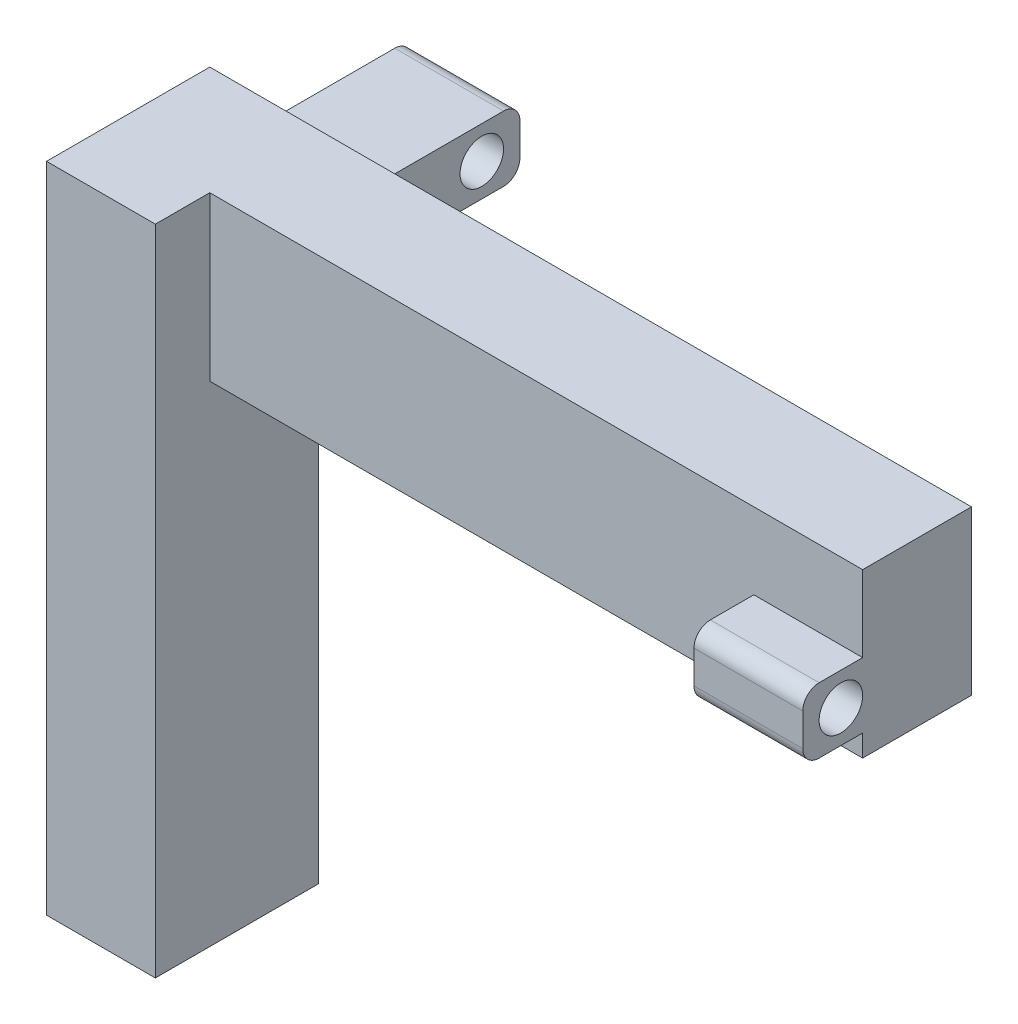
SolidWorks part; units mm, degrees
ref_plane "Front Plane" through (0, 0, 0) normal (0, 0, 1) x (1, 0, 0)
ref_plane "Top Plane" through (0, 0, 0) normal (0, 1, 0) x (1, 0, 0)
ref_plane "Right Plane" through (0, 0, 0) normal (1, 0, 0) x (0, 0, -1)
sketch "Sketch1" plane through (0, 0, 0) normal (0, 0, 1) x (1, 0, 0)
  line L1 (-5, 30) -> (5, 30)
  line L2 (-5, 30) -> (-5, -30)
  line L3 (-5, -30) -> (5, -30)
  line L4 (5, 30) -> (5, -30)
  line L5 (-5, 30) -> (5, -30) construction
  line L6 (-5, -30) -> (5, 30) construction
  point P0 (0, 0)
  dimension "D1" = 60
  dimension "D2" = 10
extrude "Boss-Extrude1" add sketch "Sketch1" along normal blind 15
sketch "Sketch2" plane through (0, 0, 0) normal (0, 0, 1) x (1, 0, 0)
  line L0 (5, 30) -> (-5, 30)
  line L1 (-5, 30) -> (-5, -30)
  line L2 (-5, -30) -> (5, -30)
  line L3 (5, -30) -> (5, 30)
ref_plane "Plane1" through (5, 0, 0) normal (1, 0, 0) x (0, 0, -1)
sketch "Sketch4" plane through (5, 0, 0) normal (1, 0, 0) x (0, 0, -1)
  line L0 (0, 30) -> (-10, 30)
  line L1 (-15, 30) -> (0, 30) construction
  line L2 (0, 30) -> (0, 15)
  line L3 (0, -30) -> (0, 30) construction
  line L4 (-10, 30) -> (-10, 15)
  line L5 (-10, 15) -> (0, 15)
  dimension "D1" = 10
  dimension "D2" = 15
extrude "Boss-Extrude2" add sketch "Sketch4" along normal blind 60
ref_plane "Plane2" through (65, 0, 0) normal (1, 0, 0) x (0, 0, -1)
sketch "Sketch5" plane through (65, 0, 0) normal (1, 0, 0) x (0, 0, -1)
  line L0 (-10, 30) -> (-10, 20)
  line L1 (-10, 30) -> (-10, 15) construction
  line L2 (-10, 20) -> (-12, 20)
  line L3 (-10, 20) -> (-14, 20)
  line L6 (-15.5, 21.5) -> (-15.5, 18.5)
  line L7 (-14, 23) -> (-10, 23)
  line L8 (-14, 17) -> (-10, 17)
  line L9 (-10, 17) -> (-10, 23)
  circle A1 centre (-12, 20) radius 2
  arc A2 (-14, 23) -> (-15.5, 21.5) centre (-14, 21.5) ccw
  arc A3 (-14, 17) -> (-15.5, 18.5) centre (-14, 18.5) cw
  dimension "D1" = 10
  dimension "D2" = 2
  dimension "D3" = 3
  dimension "D4" = 3
extrude "Boss-Extrude4" add sketch "Sketch5" against normal blind 10 contours A3 L8 L9 A1 L0 L7 A2 L6 | L2 A1 L3 | L3 A1 L2
sketch "Sketch6" plane through (65, 0, 0) normal (1, 0, 0) x (0, 0, -1)
  line L0 (-10, 23) -> (-10, 17)
  line L1 (-10, 20) -> (-12, 20)
  circle A0 centre (-12, 20) radius 2
  dimension "D1" = 2
extrude "Cut-Extrude1" cut sketch "Sketch6" against normal blind 10
ref_plane "Plane3" through (-5, 0, 0) normal (1, 0, 0) x (0, 0, -1)
sketch "Sketch7" plane through (-5, 0, 0) normal (1, 0, 0) x (0, 0, -1)
  line L0 (0, 30) -> (0, 20)
  line L1 (0, 30) -> (0, -30) construction
  line L2 (0, 20) -> (5, 20)
  line L6 (10, 23) -> (0, 23)
  line L7 (10, 17) -> (0, 17)
  line L8 (0, 30) -> (0, -30) construction
  line L9 (0, 17) -> (0, 23)
  line L11 (13, 20) -> (15, 20)
  line L12 (18.5, 18.5) -> (18.5, 21.5)
  line L13 (17, 23) -> (10, 23)
  line L14 (17, 17) -> (10, 17)
  circle A3 centre (15, 20) radius 2
  arc A4 (17, 23) -> (18.5, 21.5) centre (17, 21.5) cw
  arc A5 (17, 17) -> (18.5, 18.5) centre (17, 18.5) ccw
  point P10 (7, 20)
  point P15 (17, 20)
  dimension "D3" = 10
  dimension "D6" = 4
  dimension "D1" = 10
  dimension "D2" = 5
  dimension "D4" = 6
  dimension "D7" = 6
extrude "Boss-Extrude6" add sketch "Sketch7" along normal blind 10
